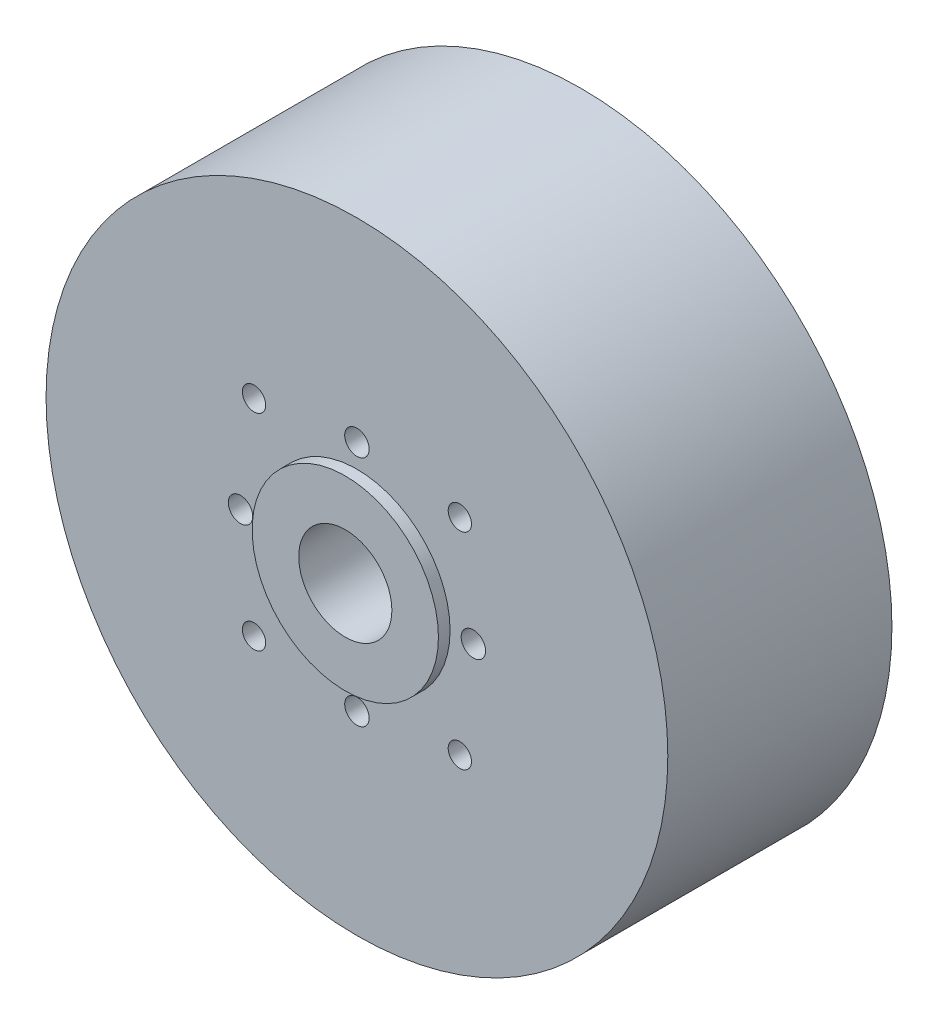
SolidWorks part; units mm, degrees
ref_plane "Front Plane" through (0, 0, 0) normal (0, 0, 1) x (1, 0, 0)
ref_plane "Top Plane" through (0, 0, 0) normal (0, 1, 0) x (1, 0, 0)
ref_plane "Right Plane" through (0, 0, 0) normal (1, 0, 0) x (0, 0, -1)
sketch "Sketch3" plane through (0, 0, 0) normal (0, 0, 1) x (1, 0, 0)
  circle A0 centre (0, 0) radius 53.4
  dimension "D1" = 106.8
extrude "Boss-Extrude1" add sketch "Sketch3" against normal blind 38.5
sketch "Sketch4" plane through (0, 0, 0) normal (0, 0, 1) x (1, 0, 0)
  circle A0 centre (0, 0) radius 8
  dimension "D1" = 16
extrude "Cut-Extrude1" cut sketch "Sketch4" against normal through all
sketch "Sketch5" plane through (0, 0, 0) normal (0, 0, 1) x (1, 0, 0)
  line L0 (0, 0) -> (-17.6777, 17.6777) construction
  line L1 (0, 0) -> (0, 25) construction
  line L2 (0, 0) -> (17.6777, -17.6777) construction
  line L3 (0, 0) -> (17.6777, 17.6777) construction
  line L4 (0, 0) -> (-17.6777, -17.6777) construction
  arc A0 (-19.0342, -16.208) -> (-16.208, -19.0342) centre (0, 0) ccw
  circle A1 centre (-17.6777, 17.6777) radius 2
  circle A2 centre (17.6777, 17.6777) radius 2
  circle A3 centre (-17.6777, -17.6777) radius 2
  circle A4 centre (17.6777, -17.6777) radius 2
  point P1 (0, 0)
  point P12 (0, 0)
  dimension "D1" = 50
  dimension "D4" = 4
  dimension "D5" = 4
  dimension "D6" = 4
  dimension "D7" = 4
  dimension "D2" = 45
  dimension "D3" = 45
extrude "Cut-Extrude2" cut sketch "Sketch5" against normal blind 20 contours A4 | A2 | A1 | A3
sketch "Sketch6" plane through (0, 0, 0) normal (0, 0, 1) x (1, 0, 0)
  circle A0 centre (0, 0) radius 16
  circle A1 centre (0, 0) radius 8
  dimension "D1" = 32
  dimension "D2" = 16
extrude "Boss-Extrude3" add sketch "Sketch6" along normal blind 2
sketch "Sketch7" plane through (0, 0, 0) normal (0, 0, 1) x (1, 0, 0)
  line L0 (0, 0) -> (20, 0) construction
  line L1 (0, 0) -> (0, 20) construction
  arc A0 (-19.8898, 2.0971) -> (-19.8898, -2.0971) centre (0, 0) ccw
  circle A1 centre (0, 20) radius 2.1
  circle A2 centre (20, 0) radius 2.1
  circle A3 centre (-20, 0) radius 2.1
  circle A4 centre (0, -20) radius 2.1
  arc A5 (-2.0971, -19.8898) -> (2.0971, -19.8898) centre (0, 0) ccw
  arc A6 (19.8898, -2.0971) -> (19.8898, 2.0971) centre (0, 0) ccw
  arc A7 (2.0971, 19.8898) -> (-2.0971, 19.8898) centre (0, 0) ccw
  dimension "D1" = 40
  dimension "D2" = 4.2
  dimension "D3" = 4.2
  dimension "D4" = 4.2
  dimension "D5" = 4.2
extrude "Cut-Extrude3" cut sketch "Sketch7" against normal blind 20 contours A4 | A2 | A1 | A3
sketch "Sketch8" plane through (0, 0, -38.5) normal (0, 0, -1) x (-1, 0, 0)
  line L0 (0, 27.5) -> (0, 30) construction
  line L1 (0, 0) -> (0, -30) construction
  line L2 (27.5, 0) -> (30, 0) construction
  line L3 (0, 0) -> (-30, 0) construction
  arc A0 (-29.8958, 2.4978) -> (-29.8958, -2.4978) centre (0, 0) ccw
  circle A1 centre (0, 30) radius 2.5
  circle A2 centre (30, 0) radius 2.5
  circle A3 centre (0, -30) radius 2.5
  circle A4 centre (-30, 0) radius 2.5
  arc A5 (2.4978, 29.8958) -> (-2.4978, 29.8958) centre (0, 0) ccw
  arc A6 (29.8958, -2.4978) -> (29.8958, 2.4978) centre (0, 0) ccw
  arc A7 (-2.4978, -29.8958) -> (2.4978, -29.8958) centre (0, 0) ccw
  dimension "D1" = 60
  dimension "D2" = 5
  dimension "D3" = 5
  dimension "D4" = 5
  dimension "D5" = 5
extrude "Cut-Extrude4" cut sketch "Sketch8" against normal blind 20 contours A4 | A1 | A2 | A3
